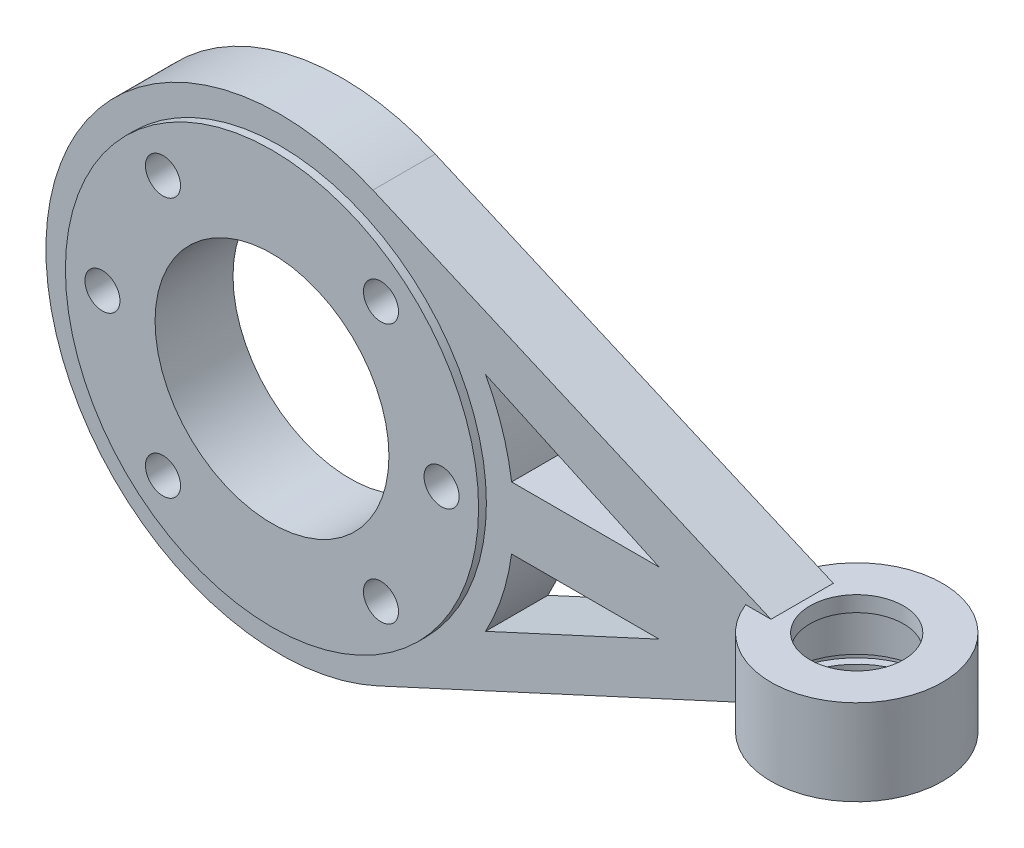
SolidWorks part; units mm, degrees
material "6061 合金"
ref_plane "前视基准面" through (0, 0, 0) normal (0, 0, 1) x (1, 0, 0)
ref_plane "上视基准面" through (0, 0, 0) normal (0, 1, 0) x (1, 0, 0)
ref_plane "右视基准面" through (0, 0, 0) normal (1, 0, 0) x (0, 0, -1)
other "Configuration Table"
sketch "草图1" plane through (0, 0, 0) normal (0, 0, 1) x (1, 0, 0)
  circle A0 centre (0, 0) radius 30
  dimension "D1" = 60
extrude "凸台-拉伸1" add sketch "草图1" along normal blind 3
sketch "草图2" plane through (0, 0, 3) normal (0, 0, 1) x (1, 0, 0)
  line L0 (0, 0) -> (150.9371, 0) construction
  line L1 (70, 22.7173) -> (70, -21.6499) construction
  line L3 (59, 5.375) -> (70, 5.375)
  line L4 (59, 5.375) -> (59, -5.625)
  line L8 (59, -5.625) -> (70, -5.625)
  line L9 (70, 5.375) -> (70, -5.625)
  dimension "D2" = 11
  dimension "D1" = 70
  dimension "D3" = 5.375
  dimension "D4" = 11
revolve "旋转1" add sketch "草图2" angle 360 about L1
sketch "草图3" plane through (0, 0, 3) normal (0, 0, 1) x (1, 0, 0)
  line L0 (11.9376, 27.5226) -> (63, 5.375)
  line L1 (12.5558, -27.2461) -> (63, -4)
  line L2 (70, -5.625) -> (70, 5.375) construction
  line L4 (63, 5.375) -> (63, -4)
  circle A1 centre (0, 0) radius 30
  arc A2 (11.9376, 27.5226) -> (12.5558, -27.2461) centre (0, 0) ccw
  dimension "D2" = 7
  dimension "D3" = 5.375
  dimension "D4" = 4
  dimension "D1" = 0
extrude "凸台-拉伸2" add sketch "草图3" along normal mid plane 8
sketch "草图4" plane through (0, -5.625, 0) normal (0, -1, 0) x (1, 0, 0)
  circle A0 centre (70, 3) radius 6
  dimension "D1" = 12
extrude "切除-拉伸1" cut sketch "草图4" against normal blind 25
sketch "草图5" plane through (0, -5.625, 0) normal (0, -1, 0) x (1, 0, 0)
  circle A0 centre (70, 3) radius 9
  dimension "D1" = 18
extrude "切除-拉伸2" cut sketch "草图5" against normal offset from surface (9 mm away) 2 up to face at (70, 5.375, 9)
sketch "草图6" plane through (0, 3.375, 0) normal (0, -1, 0) x (1, 0, 0)
  circle A0 centre (70, 3) radius 10
  circle A1 centre (70, 3) radius 9 construction
  circle A2 centre (70, 3) radius 9 construction
  circle A3 centre (70, 3) radius 9
  circle M1 centre (70, 3) radius 9
  dimension "D1" = 1
extrude "切除-拉伸3" cut sketch "草图6" along normal blind 1.1 from offset 6.75 contours A0 M1 | A3
ref_plane "基准面1" through (0, 0, 3) normal (0, 0, -1) x (-1, 0, 0)
sketch "草图8" plane through (0, 0, 3) normal (0, 0, -1) x (-1, 0, 0)
  circle A0 centre (0, 0) radius 26.5
  dimension "D1" = 53
extrude "凸台-拉伸3" add sketch "草图8" along normal mid plane 10
sketch "草图7" plane through (0, 0, 7) normal (0, 0, 1) x (1, 0, 0)
  line L0 (26.3923, -14.2634) -> (48.664, -4)
  line L1 (0, 0) -> (55.8434, 0) construction
  line L2 (12.5558, -27.2461) -> (59.753, -5.4963) construction
  line L4 (29.7321, -4) -> (48.664, -4)
  line L5 (29.7321, 4) -> (48.664, 4)
  line L6 (26.3923, 14.2634) -> (48.664, 4)
  circle A0 centre (0, 0) radius 15
  arc A1 (26.3923, -14.2634) -> (29.7321, -4) centre (0, 0) ccw
  arc A2 (26.3923, 14.2634) -> (29.7321, 4) centre (0, 0) cw
  dimension "D1" = 30
  dimension "D3" = 30
  dimension "D2" = 6
  dimension "D4" = 4
extrude "切除-拉伸4" cut sketch "草图7" against normal through all both and the other way through all
fillet "圆角1" [suppressed] radius 2
sketch "草图10" plane through (0, 0, 8) normal (0, 0, 1) x (1, 0, 0)
  line L0 (-42.7659, 0) -> (30.817, 0) construction
  line L1 (0, 0) -> (27.9613, -33.3229) construction
  line L2 (0, 31.5638) -> (0, -40.9894) construction
  circle A0 centre (21.75, 0) radius 2.25
  circle A1 centre (13.9806, -16.6615) radius 2.25
  circle A2 centre (-21.75, 0) radius 2.25
  circle A3 centre (-13.9806, -16.6615) radius 2.25
  circle A4 centre (13.9806, 16.6615) radius 2.25
  circle A5 centre (-13.9806, 16.6615) radius 2.25
  dimension "D2" = 4.5
  dimension "D3" = 4.5
  dimension "D1" = 50
  dimension "D4" = 21.75
  dimension "D5" = 21.75
extrude "切除-拉伸5" cut sketch "草图10" against normal blind 17
